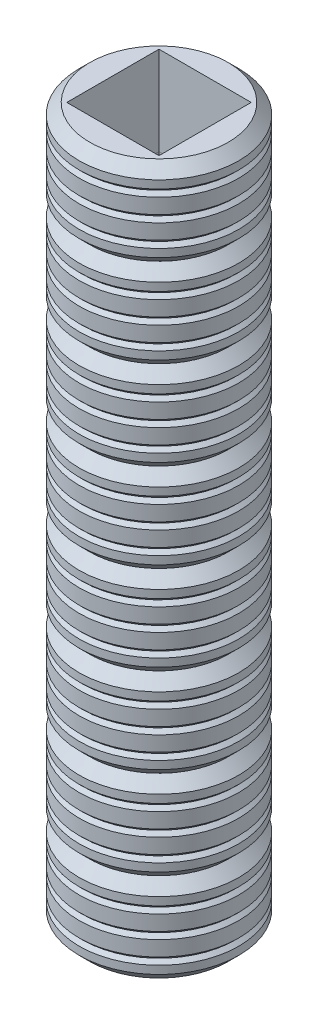
SolidWorks part; units mm, degrees
ref_plane "Front Plane" through (0, 0, 0) normal (0, 0, 1) x (1, 0, 0)
ref_plane "Top Plane" through (0, 0, 0) normal (0, 1, 0) x (1, 0, 0)
ref_plane "Right Plane" through (0, 0, 0) normal (1, 0, 0) x (0, 0, -1)
sketch "Sketch1" plane through (0, 0, 0) normal (0, 1, 0) x (1, 0, 0)
  line L1 (-3.302, -3.302) -> (3.302, -3.302)
  line L2 (-3.302, -3.302) -> (-3.302, 3.302)
  line L3 (-3.302, 3.302) -> (3.302, 3.302)
  line L4 (3.302, -3.302) -> (3.302, 3.302)
  line L5 (-3.302, -3.302) -> (3.302, 3.302) construction
  line L6 (-3.302, 3.302) -> (3.302, -3.302) construction
  circle A0 centre (0, 0) radius 5.715
  dimension "D1" = 11.43
  dimension "D2" = 6.604
  dimension "D3" = 6.604
extrude "Boss-Extrude1" add sketch "Sketch1" along normal mid plane 1.5875
sketch "Sketch2" plane through (0, 0, 0) normal (0, 0, 1) x (1, 0, 0)
  line L0 (0, 0) -> (0, 7.1335) construction
chamfer "Chamfer1" distance 0.254 angle 45 2 edges at (0, -0.7937, 5.715) (0, 0.7937, 5.715)
pattern_linear "LPattern1" count 2 spacing 1.5875 along (0, 1, 0) count 3 spacing 1.5875 along (0, -1, 0) of bodies 101
sketch "Sketch3" plane through (0, 0, 0) normal (1, 0, 0) x (0, 0, -1)
  line L0 (-4.953, 2.3812) -> (-5.848, 1.4863)
  line L1 (5.461, 2.3812) -> (-5.461, 2.3812) construction
  line L2 (-5.848, 1.4863) -> (-5.848, 3.2762)
  line L3 (-5.848, 3.2762) -> (-4.953, 2.3812)
  line L4 (-5.715, 2.1273) -> (-5.715, 1.0477) construction
  line L5 (0, -0.7937) -> (-5.461, -0.7938) construction
  line L6 (5.461, -0.7937) -> (-5.461, -0.7937) construction
  line L7 (-5.715, -0.5398) -> (-5.461, -0.7937) construction
  line L8 (-5.848, -3.0738) -> (-5.848, -4.8637)
  line L9 (-4.953, -3.9688) -> (-5.848, -3.0738)
  line L10 (-5.848, -4.8637) -> (-4.953, -3.9688)
  dimension "D1" = 0.762
revolve "Cut-Revolve3" cut sketch "Sketch3" angle 360 about L0
combine bodies "Combine1" operation type add bodies to combine 101 106 103 105
pattern_linear "LPattern2" count 8 spacing 6.35 along (0, -1, 0) of bodies 107
